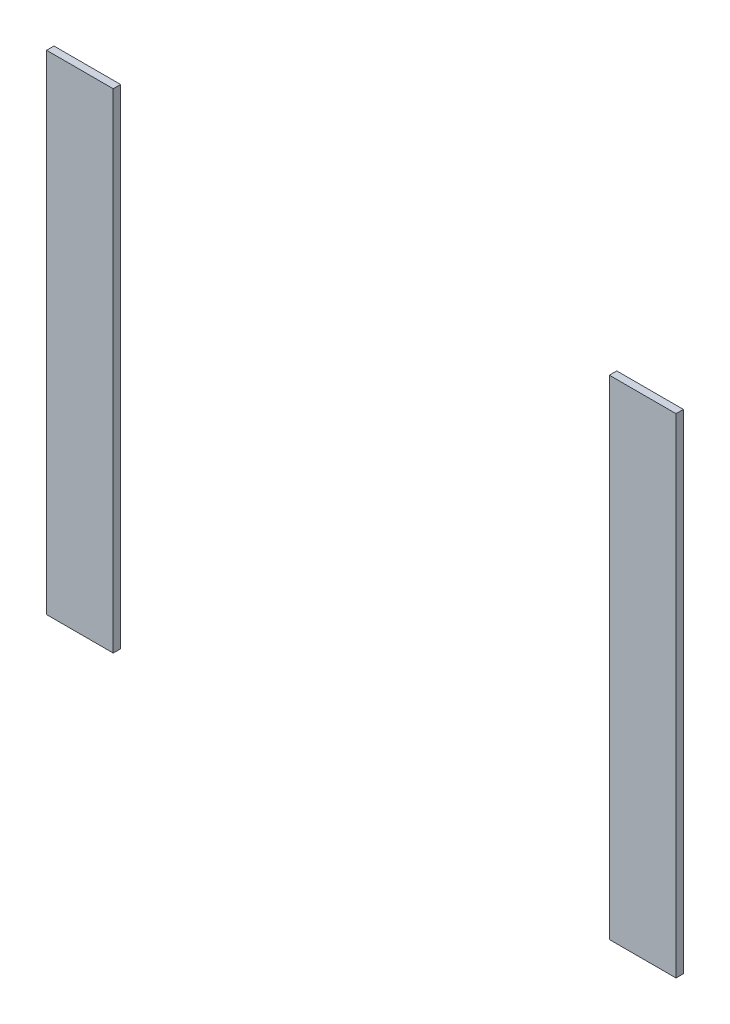
SolidWorks part; units mm, degrees
ref_plane "Front Plane" through (0, 0, 0) normal (0, 0, 1) x (1, 0, 0)
ref_plane "Top Plane" through (0, 0, 0) normal (0, 1, 0) x (1, 0, 0)
ref_plane "Right Plane" through (0, 0, 0) normal (1, 0, 0) x (0, 0, -1)
sketch "Sketch1" plane through (0, 0, 0) normal (0, 0, 1) x (1, 0, 0)
  line L0 (-425, 615) -> (425, 615)
  line L6 (-335, 285) -> (335, 285)
  line L9 (-425, -45) -> (-335, -45)
  line L10 (-425, -45) -> (-425, 615)
  line L11 (-425, 615) -> (-335, 615)
  line L12 (-335, -45) -> (-335, 615)
  line L13 (425, -45) -> (335, -45)
  line L14 (425, -45) -> (425, 615)
  line L15 (425, 615) -> (335, 615)
  line L16 (335, -45) -> (335, 615)
  point P0 (0, 0)
extrude "Boss-Extrude1" add sketch "Sketch1" along normal blind 10 contours L9 L12 L0 L10 | L16 L13 L14 L0
